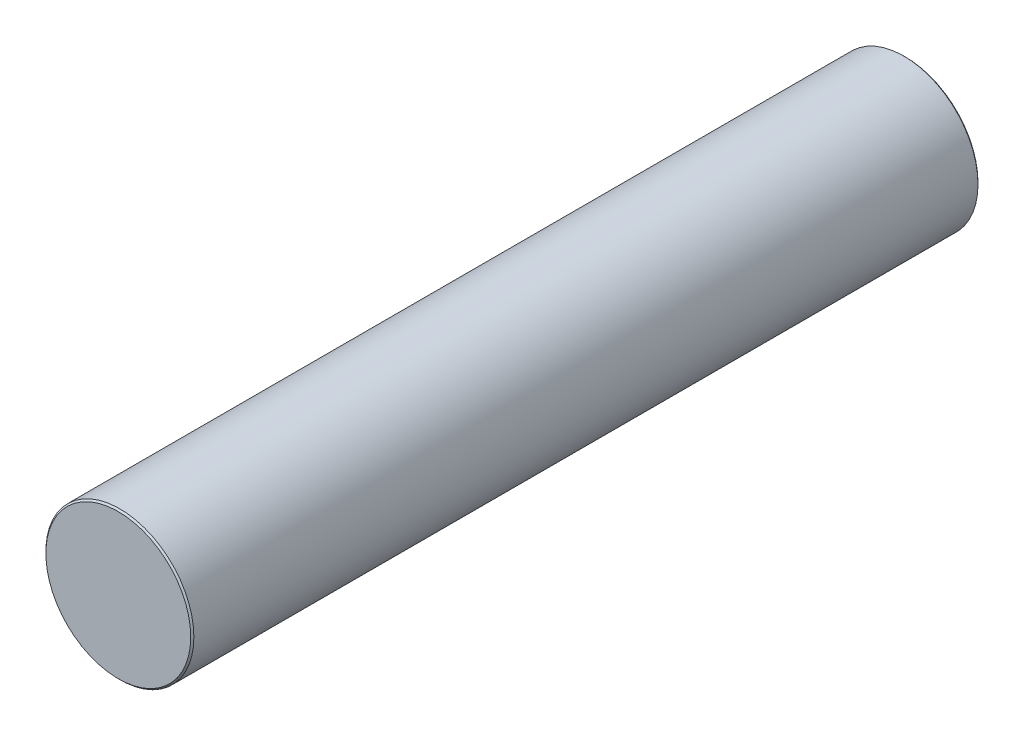
SolidWorks part; units mm, degrees
ref_plane "Front Plane" through (0, 0, 0) normal (0, 0, 1) x (1, 0, 0)
ref_plane "Top Plane" through (0, 0, 0) normal (0, 1, 0) x (1, 0, 0)
ref_plane "Right Plane" through (0, 0, 0) normal (1, 0, 0) x (0, 0, -1)
sketch "Sketch2" plane through (0, 0, 0) normal (0, 0, 1) x (1, 0, 0)
  circle A0 centre (0, 0) radius 2.35
  dimension "D1" = 4.7
extrude "Boss-Extrude1" add sketch "Sketch2" along normal blind 25
chamfer "Chamfer2" distance 0.05 angle 45 2 edges at (2.35, 0, 25) (2.35, 0, 0)
